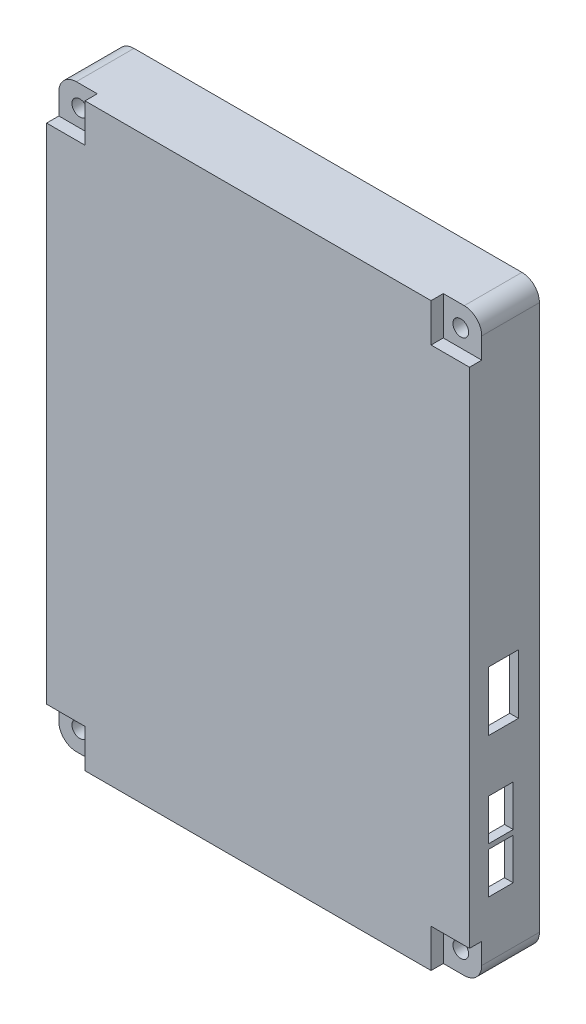
SolidWorks part; units mm, degrees
ref_plane "Piano frontale" through (0, 0, 0) normal (0, 0, 1) x (1, 0, 0)
ref_plane "Piano superiore" through (0, 0, 0) normal (0, 1, 0) x (1, 0, 0)
ref_plane "Piano destro" through (0, 0, 0) normal (1, 0, 0) x (0, 0, -1)
sketch "Schizzo1" plane through (0, 0, 0) normal (0, 0, 1) x (1, 0, 0)
  line L0 (-60.5, -83) -> (60.5, 83) construction
  line L1 (-60.5, 83) -> (60.5, 83)
  line L2 (-60.5, 83) -> (-60.5, -83)
  line L3 (-60.5, -83) -> (60.5, -83)
  line L4 (60.5, 83) -> (60.5, -83)
  dimension "D1" = 121
  dimension "D2" = 166
extrude "Estrusione-Estrusione1" add sketch "Schizzo1" along normal blind 20
fillet "Raccordo1" radius 5 4 edges at (60.5, -83, 10) (-60.5, -83, 10) (-60.5, 83, 10) (60.5, 83, 10)
sketch "Schizzo2" plane through (0, 0, 0) normal (0, 0, -1) x (-1, 0, 0)
  line L1 (-55.5, 83) -> (55.5, 83) construction
  line L2 (60.5, 78) -> (60.5, -78) construction
  line L3 (-60.5, -78) -> (-60.5, 78) construction
  line L4 (55.5, -83) -> (-55.5, -83) construction
  line L7 (-51.5, 80) -> (51.5, 80)
  line L9 (-51.5, -80) -> (51.5, -80)
  line L10 (-57.5, 74) -> (-57.5, -74)
  line L11 (-51.5, 80) -> (-51.5, 74)
  line L12 (-51.5, 74) -> (-57.5, 74)
  line L13 (51.5, 80) -> (51.5, 74)
  line L14 (51.5, 74) -> (57.5, 74)
  line L15 (51.5, -80) -> (51.5, -74)
  line L16 (51.5, -74) -> (57.5, -74)
  line L17 (-51.5, -80) -> (-51.5, -74)
  line L18 (-51.5, -74) -> (-57.5, -74)
  line L19 (57.5, 74) -> (57.5, -74)
  point P9 (-49, 65)
  point P10 (49, 65)
  point P11 (49, -65)
  point P12 (-49, -65)
  dimension "D2" = 6
  dimension "D3" = 6
  dimension "D4" = 6
  dimension "D5" = 6
  dimension "D6" = 6
  dimension "D7" = 6
  dimension "D8" = 6
  dimension "D9" = 6
  dimension "D10" = 3
  dimension "D11" = 3
  dimension "D1" = 3
  dimension "D12" = 3
extrude "Taglio-Estrusione1" cut sketch "Schizzo2" against normal blind 14.5
sketch "Schizzo3" plane through (0, 0, 0) normal (0, 0, -1) x (-1, 0, 0)
  line L0 (-54.5, 74) -> (-54.5, 83) construction
  line L1 (-51.5, 74) -> (-57.5, 74) construction
  line L2 (-55.5, 83) -> (55.5, 83) construction
  line L3 (-51.5, 77) -> (-60.5, 77) construction
  line L4 (-51.5, 80) -> (-51.5, 74) construction
  line L5 (-60.5, -78) -> (-60.5, 78) construction
  line L6 (54.5, 74) -> (54.5, 83) construction
  line L7 (57.5, 74) -> (51.5, 74) construction
  line L8 (51.5, 77) -> (60.5, 77) construction
  line L9 (51.5, 74) -> (51.5, 80) construction
  line L10 (60.5, 78) -> (60.5, -78) construction
  line L11 (51.5, -77) -> (60.5, -77) construction
  line L12 (51.5, -80) -> (51.5, -74) construction
  line L13 (54.5, -74) -> (54.5, -83) construction
  line L14 (51.5, -74) -> (57.5, -74) construction
  line L15 (55.5, -83) -> (-55.5, -83) construction
  line L16 (-54.5, -74) -> (-54.5, -83) construction
  line L17 (-57.5, -74) -> (-51.5, -74) construction
  line L18 (-51.5, -77) -> (-60.5, -77) construction
  line L19 (-51.5, -74) -> (-51.5, -80) construction
  circle A0 centre (-54.5, 77) radius 2.25
  circle A1 centre (54.5, 77) radius 2.25
  circle A2 centre (54.5, -77) radius 2.25
  circle A3 centre (-54.5, -77) radius 2.25
  dimension "D1" = 4.5
  dimension "D2" = 4.5
  dimension "D3" = 4.5
  dimension "D4" = 4.5
extrude "Taglio-Estrusione2" cut sketch "Schizzo3" against normal through all
sketch "Schizzo4" plane through (0, 0, 0) normal (0, 0, -1) x (-1, 0, 0)
  line L0 (-55.5, 83) -> (55.5, 83) construction
  line L1 (-55.5, 83) -> (55.5, 83) construction
  line L2 (-60.5, 78) -> (-60.5, -78) construction
  line L3 (-55.5, -83) -> (55.5, -83) construction
  line L4 (60.5, 78) -> (60.5, -78) construction
  line L5 (-60.5, -78) -> (-60.5, 78) construction
  line L6 (55.5, -83) -> (-55.5, -83) construction
  line L7 (60.5, 78) -> (60.5, -78) construction
  line L8 (-55.5, 81.5) -> (55.5, 81.5)
  line L9 (59, 78) -> (59, -78)
  line L10 (-55.5, -81.5) -> (55.5, -81.5)
  line L11 (-59, 78) -> (-59, -78)
  arc A0 (-60.5, -78) -> (-55.5, -83) centre (-55.5, -78) ccw construction
  arc A1 (60.5, -78) -> (55.5, -83) centre (55.5, -78) cw construction
  arc A2 (60.5, 78) -> (55.5, 83) centre (55.5, 78) ccw construction
  arc A3 (-60.5, 78) -> (-55.5, 83) centre (-55.5, 78) cw construction
  arc A4 (59, 78) -> (55.5, 81.5) centre (55.5, 78) ccw
  arc A5 (59, -78) -> (55.5, -81.5) centre (55.5, -78) cw
  arc A6 (-59, -78) -> (-55.5, -81.5) centre (-55.5, -78) ccw
  arc A7 (-59, 78) -> (-55.5, 81.5) centre (-55.5, 78) cw
  dimension "D1" = 5
  dimension "D2" = 1.5
extrude "Taglio-Estrusione3" cut sketch "Schizzo4" against normal blind 1.5
sketch "Schizzo5" plane through (0, 0, 20) normal (0, 0, 1) x (1, 0, 0)
  line L0 (-55.5, -83) -> (55.5, -83) construction
  line L1 (-60.5, 83) -> (-49.5, 83)
  line L2 (-60.5, 83) -> (-60.5, 72)
  line L3 (-60.5, 72) -> (-49.5, 72)
  line L4 (-49.5, 83) -> (-49.5, 72)
  line L5 (49.5, 83) -> (60.5, 83)
  line L6 (49.5, 83) -> (49.5, 72)
  line L7 (49.5, 72) -> (60.5, 72)
  line L8 (60.5, 83) -> (60.5, 72)
  line L9 (49.5, -83) -> (60.5, -83)
  line L10 (49.5, -83) -> (49.5, -72)
  line L11 (49.5, -72) -> (60.5, -72)
  line L12 (60.5, -83) -> (60.5, -72)
  line L13 (-60.5, -72) -> (-49.5, -72)
  line L14 (-60.5, -72) -> (-60.5, -83)
  line L15 (-60.5, -83) -> (-49.5, -83)
  line L16 (-49.5, -72) -> (-49.5, -83)
  line L17 (-60.5, 78) -> (-60.5, -78) construction
  line L18 (55.5, 83) -> (-55.5, 83) construction
  line L19 (60.5, -78) -> (60.5, 78) construction
  dimension "D3" = 11
  dimension "D1" = 11
  dimension "D2" = 11
  dimension "D4" = 11
  dimension "D5" = 11
  dimension "D6" = 11
  dimension "D7" = 11
  dimension "D8" = 11
extrude "Taglio-Estrusione4" cut sketch "Schizzo5" against normal blind 3.5
sketch "Schizzo6" plane through (0, 0, 14.5) normal (0, 0, -1) x (-1, 0, 0)
  line L0 (-57.5, 71) -> (-48.5, 71)
  line L1 (-48.5, 71) -> (-48.5, 80)
  line L2 (-48.5, 80) -> (48.5, 80)
  line L3 (48.5, 80) -> (48.5, 71)
  line L4 (48.5, 71) -> (57.5, 71)
  line L5 (57.5, 71) -> (57.5, -71)
  line L6 (57.5, -71) -> (48.5, -71)
  line L7 (48.5, -71) -> (48.5, -80)
  line L8 (48.5, -80) -> (-48.5, -80)
  line L9 (-48.5, -80) -> (-48.5, -71)
  line L10 (-48.5, -71) -> (-57.5, -71)
  line L11 (-57.5, -71) -> (-57.5, 71)
  line L12 (-60.5, -78) -> (-60.5, 78) construction
  line L13 (-55.5, 83) -> (55.5, 83) construction
  line L14 (60.5, 78) -> (60.5, -78) construction
  line L15 (55.5, -83) -> (-55.5, -83) construction
  line L16 (-57.5, 74) -> (-57.5, -74) construction
  line L17 (-51.5, -80) -> (51.5, -80) construction
  line L18 (57.5, -74) -> (57.5, 74) construction
  line L19 (51.5, 80) -> (-51.5, 80) construction
  dimension "D1" = 12
  dimension "D2" = 12
  dimension "D3" = 12
  dimension "D4" = 12
  dimension "D5" = 12
  dimension "D6" = 12
  dimension "D7" = 12
  dimension "D8" = 12
extrude "Taglio-Estrusione5" cut sketch "Schizzo6" against normal blind 3.5
sketch "Schizzo11" plane through (57.5, 0, 0) normal (-1, 0, 0) x (0, 0, 1)
  line L0 (20, -72) -> (20, 72) construction
  line L1 (6, -5) -> (14.5, -5)
  line L2 (6, -5) -> (6, -22)
  line L3 (6, -22) -> (14.5, -22)
  line L4 (14.5, -5) -> (14.5, -22)
  line L5 (7.5, -37) -> (14.5, -37)
  line L6 (7.5, -37) -> (7.5, -62)
  line L11 (7.5, -62) -> (14.5, -62)
  line L12 (14.5, -37) -> (14.5, -62)
  line L13 (16.5, 83) -> (0, 83) construction
  dimension "D1" = 8.5
  dimension "D2" = 7
  dimension "D3" = 25
  dimension "D4" = 5.5
  dimension "D6" = 5.5
  dimension "D7" = 17
  dimension "D10" = 88
  dimension "D11" = 15
extrude "Taglio-Estrusione9" cut sketch "Schizzo11" against normal blind 10
sketch "Schizzo12" plane through (57.5, 0, 0) normal (-1, 0, 0) x (0, 0, 1)
  line L0 (1.5, 74) -> (1.5, -74) construction
  line L1 (1.5, 3) -> (18, 3)
  line L2 (1.5, 3) -> (1.5, -70)
  line L3 (1.5, -70) -> (18, -70)
  line L4 (18, 3) -> (18, -70)
  line L5 (18, 71) -> (18, -71) construction
  line L6 (14.5, -5) -> (6, -5) construction
  line L7 (7.5, -62) -> (14.5, -62) construction
  dimension "D1" = 8
  dimension "D2" = 8
extrude "Taglio-Estrusione10" cut sketch "Schizzo12" against normal blind 0.5
sketch "Schizzo13" plane through (0, 0, 18) normal (0, 0, -1) x (-1, 0, 0)
  line L0 (22.8, -58) -> (54.5, -58) construction
  line L1 (54.5, -49.25) -> (22.8, -49.25) construction
  line L2 (54.5, -49.25) -> (54.5, -66.75) construction
  line L3 (54.5, -66.75) -> (22.8, -66.75) construction
  line L4 (22.8, -49.25) -> (22.8, -66.75) construction
  line L5 (57.5, -71) -> (57.5, 71) construction
  line L7 (-55.5, 83) -> (55.5, 83) construction
  line L8 (48.5, -71) -> (57.5, -71) construction
  circle A0 centre (54.5, -66.75) radius 1.25
  circle A1 centre (54.5, -49.25) radius 1.25
  circle A2 centre (22.8, -51.3) radius 1.425
  circle A3 centre (22.8, -64.7) radius 1.25
  circle A5 centre (54.5, -49.25) radius 2.5
  circle A6 centre (54.5, -66.75) radius 2.5
  circle A7 centre (22.8, -64.7) radius 2.5
  circle A8 centre (22.8, -51.3) radius 2.5
  dimension "D3" = 2.85
  dimension "D4" = 2.5
  dimension "D5" = 2.5
  dimension "D6" = 2.5
  dimension "D7" = 6.7
  dimension "D9" = 5
  dimension "D10" = 5
  dimension "D11" = 5
  dimension "D12" = 5
  dimension "D1" = 31.7
  dimension "D2" = 17.5
  dimension "D8" = 6.7
  dimension "D13" = 3
  dimension "D14" = 13
  dimension "D15" = 141
extrude "Estrusione-Estrusione3" add sketch "Schizzo13" along normal blind 5
sketch "Schizzo14" plane through (-60.5, 0, 0) normal (-1, 0, 0) x (0, 0, 1)
  line L0 (20, 72) -> (20, -72) construction
  line L1 (14, -64) -> (6, -64)
  line L2 (14, -64) -> (14, -52)
  line L3 (14, -52) -> (6, -52)
  line L4 (6, -64) -> (6, -52)
  line L7 (6, -58) -> (14, -58) construction
  line L8 (0, 83) -> (16.5, 83) construction
  dimension "D1" = 12
  dimension "D2" = 8
  dimension "D3" = 6
  dimension "D4" = 141
extrude "Taglio-Estrusione11" cut sketch "Schizzo14" against normal blind 3
sketch "Schizzo15" plane through (-57.5, 0, 0) normal (1, 0, 0) x (0, 0, -1)
  line L0 (-18, -71) -> (-18, 71) construction
  line L1 (-18, 21.5) -> (-14, 21.5)
  line L2 (-18, 21.5) -> (-18, 14.5)
  line L3 (-18, 14.5) -> (-14, 14.5)
  line L4 (-14, 21.5) -> (-14, 14.5)
  line L5 (-14.5, 74) -> (-1.5, 74) construction
  dimension "D1" = 4
  dimension "D2" = 7
  dimension "D3" = 52.5
extrude "Taglio-Estrusione12" cut sketch "Schizzo15" against normal blind 3
sketch "Schizzo16" plane through (0, 0, 18) normal (0, 0, -1) x (-1, 0, 0)
  line L0 (57.5, 21.5) -> (57.5, 71) construction
  line L1 (57.5, 24.8) -> (53.5, 24.8)
  line L2 (57.5, 24.8) -> (57.5, 22.8)
  line L3 (57.5, 22.8) -> (53.5, 22.8)
  line L4 (53.5, 24.8) -> (53.5, 22.8)
  line L5 (57.5, -71) -> (57.5, 14.5) construction
  line L6 (57.5, 13.2) -> (53.5, 13.2)
  line L7 (57.5, 13.2) -> (57.5, 11.2)
  line L8 (57.5, 11.2) -> (53.5, 11.2)
  line L9 (53.5, 13.2) -> (53.5, 11.2)
  dimension "D1" = 1.3
  dimension "D2" = 1.3
  dimension "D3" = 4
  dimension "D4" = 4
  dimension "D5" = 2
  dimension "D6" = 2
extrude "Estrusione-Estrusione4" add sketch "Schizzo16" along normal blind 3
sketch "Schizzo17" plane through (-60.5, 0, 0) normal (-1, 0, 0) x (0, 0, 1)
  line L0 (18, -70) -> (18, 3) construction
  line L1 (18, 13.5) -> (13, 13.5)
  line L2 (18, 13.5) -> (18, 22.5)
  line L3 (18, 22.5) -> (13, 22.5)
  line L4 (13, 13.5) -> (13, 22.5)
  line L5 (14, 21.5) -> (18, 21.5) construction
  line L6 (18, 14.5) -> (14, 14.5) construction
  line L7 (14, 14.5) -> (14, 21.5) construction
  dimension "D1" = 1
  dimension "D2" = 1
  dimension "D3" = 1
extrude "Taglio-Estrusione13" cut sketch "Schizzo17" against normal blind 1
sketch "Schizzo18" plane through (0, 0, 14.5) normal (0, 0, -1) x (-1, 0, 0)
  line L1 (-58, -49.5) -> (-60.5, -49.5) construction
  line L2 (-58, -37) -> (-58, -62) construction
  line L3 (-60.5, -62) -> (-60.5, -37) construction
  line L6 (-58, -48.8) -> (-60.5, -48.8)
  line L7 (-58, -48.8) -> (-58, -50.2)
  line L8 (-58, -50.2) -> (-60.5, -50.2)
  line L9 (-60.5, -48.8) -> (-60.5, -50.2)
  dimension "D1" = 0.7
  dimension "D2" = 0.7
extrude "Estrusione-Estrusione5" add sketch "Schizzo18" along normal blind 10
